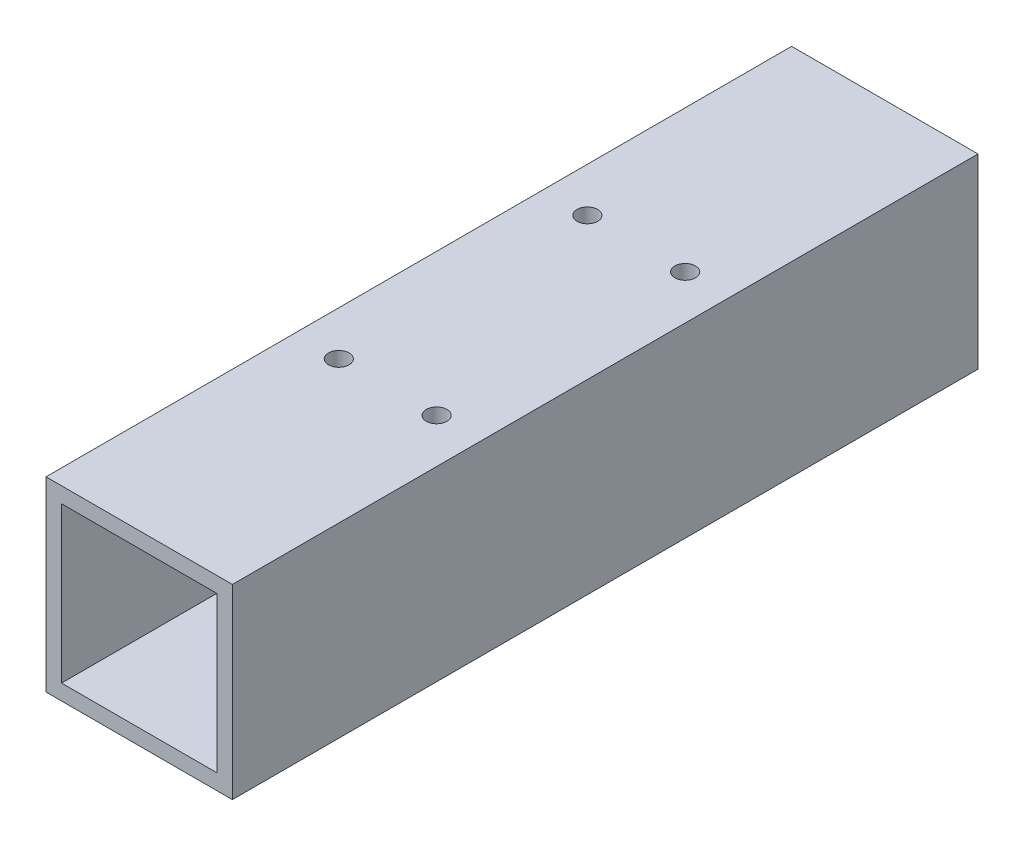
SolidWorks part; units mm, degrees
material "1060 Alloy"
ref_plane "Front Plane" through (0, 0, 0) normal (0, 0, 1) x (1, 0, 0)
ref_plane "Top Plane" through (0, 0, 0) normal (0, 1, 0) x (1, 0, 0)
ref_plane "Right Plane" through (0, 0, 0) normal (1, 0, 0) x (0, 0, -1)
sketch "Sketch1" plane through (0, 0, 0) normal (0, 0, 1) x (1, 0, 0)
  line L0 (-31.75, 31.75) -> (31.75, 31.75)
  line L2 (-38.1, 38.1) -> (38.1, 38.1)
  line L3 (-38.1, 38.1) -> (-38.1, -38.1)
  line L4 (-38.1, -38.1) -> (38.1, -38.1)
  line L5 (38.1, 38.1) -> (38.1, -38.1)
  line L10 (31.75, 31.75) -> (31.75, -31.75)
  line L11 (-31.75, -31.75) -> (31.75, -31.75)
  line L12 (-31.75, 31.75) -> (-31.75, -31.75)
  point P12 (0, 38.1)
  point P14 (38.1, 0)
  dimension "Wall Thickness" = 6.35
  dimension "Outside Width" = 76.2
  dimension "Outside Height" = 76.2
  dimension "Inside Height" = 63.5
  dimension "Inside Width" = 63.5
sketch "Sketch2" plane through (0, 0, 0) normal (1, 0, 0) x (0, 0, -1)
  line L0 (152.4, 0) -> (-152.4, 0)
  point P4 (0, 0)
  point P7 (-152.4, 0)
  point P10 (152.4, 0)
  dimension "Length" = 304.8
sketch "Sketch3" plane through (0, 0, 0) normal (0, 0, 1) x (1, 0, 0)
  line L21 (38.1, 38.1) -> (-38.1, 38.1)
  line L22 (38.1, -38.1) -> (38.1, 38.1)
  line L23 (-38.1, -38.1) -> (38.1, -38.1)
  line L24 (-38.1, 38.1) -> (-38.1, -38.1)
  line L25 (38.1, 38.1) -> (-38.1, 38.1)
  line L26 (38.1, -38.1) -> (38.1, 38.1)
  line L27 (-38.1, -38.1) -> (38.1, -38.1)
  line L28 (-38.1, 38.1) -> (-38.1, -38.1)
  line L29 (31.75, 31.75) -> (-31.75, 31.75)
  line L30 (31.75, -31.75) -> (31.75, 31.75)
  line L31 (-31.75, -31.75) -> (31.75, -31.75)
  line L32 (-31.75, 31.75) -> (-31.75, -31.75)
  line L33 (31.75, 31.75) -> (-31.75, 31.75)
  line L34 (31.75, -31.75) -> (31.75, 31.75)
  line L35 (-31.75, -31.75) -> (31.75, -31.75)
  line L36 (-31.75, 31.75) -> (-31.75, -31.75)
  dimension "D1" = 0
  dimension "D2" = 0
extrude "Boss-Extrude1" add sketch "Sketch3" along normal up to vertex (152.4 mm away) and the other way up to vertex (152.4 mm away) up to point (0, 0, 152.4) other way up to point (0, 0, -152.4)
sketch "Drawing Reference" plane through (0, 0, 0) normal (1, 0, 0) x (0, 0, -1)
  line L0 (-152.4, 0) -> (152.4, 0) construction
  line L1 (0, -38.1) -> (0, 38.1) construction
  line L2 (-152.4, -38.1) -> (152.4, -38.1) construction
  line L5 (-152.4, 38.1) -> (152.4, 38.1) construction
  point P7 (-129.54, 0)
  point P8 (129.54, 0)
  dimension "D1" = 22.86
hole_wizard "5/16 Clearance Hole3" positions "Sketch12" profile "Sketch13" hole size "5/16" standard "ANSI Inch" end condition through all
sketch "Sketch12" plane through (0, -38.1, 0) normal (0, -1, 0) x (-1, 0, 0)
  line L1 (-20, -50.8) -> (20, -50.8)
  line L2 (-20, -50.8) -> (-20, 50.8)
  line L3 (-20, 50.8) -> (20, 50.8)
  line L4 (20, -50.8) -> (20, 50.8)
  line L5 (-20, -50.8) -> (20, 50.8) construction
  line L6 (-20, 50.8) -> (20, -50.8) construction
  point P2 (20, 50.8)
  point P127 (-20, -50.8)
  point P128 (-20, 50.8)
  point P129 (20, -50.8)
  point P143 (0, 0)
  dimension "D1" = 101.6
  dimension "D2" = 40
sketch "Sketch13" plane through (-20, -38.1, -50.8) normal (1, 0, 0) x (0, 0, -1)
  line L0 (0, 0) -> (0, 76.2)
  line L1 (0, 76.2) -> (4.2164, 76.2)
  line L2 (4.2164, 76.2) -> (4.2164, 0)
  line L5 (4.2164, 0) -> (0, 0)
  line L11 (0, -6.35) -> (0, 107.95) construction
  dimension "Thru Hole Dia." = 8.4328
  dimension "Thru Hole Depth" = 76.2
hole_wizard "1/2 Clearance Hole1" positions "Sketch14" profile "Sketch15" hole size "1/2" standard "ANSI Inch"
sketch "Sketch14" plane through (0, -38.1, 0) normal (0, -1, 0) x (-1, 0, 0)
  point P0 (-20, 50.8)
  point P3 (20, 50.8)
  point P6 (-20, -50.8)
  point P9 (20, -50.8)
sketch "Sketch15" plane through (20, -38.1, -50.8) normal (1, 0, 0) x (0, 0, -1)
  line L0 (0, 0) -> (0, 10.4035)
  line L1 (0, 10.4035) -> (6.7462, 6.35)
  line L2 (6.7462, 6.35) -> (6.7462, 0)
  line L5 (6.7462, 0) -> (0, 0)
  line L10 (0, 10.4035) -> (-6.7462, 6.35) construction
  line L11 (0, -6.35) -> (0, 107.95) construction
  dimension "Hole Dia." = 13.4925
  dimension "Hole Depth" = 6.35
  dimension "Drill Angle" = 118
sketch "Sketch16" plane through (0, -38.1, 0) normal (0, -1, 0) x (1, 0, 0)
  line L0 (0, -152.4) -> (0, 152.4) construction
  line L1 (-38.1, -152.4) -> (38.1, -152.4) construction
  line L2 (-38.1, 152.4) -> (38.1, 152.4) construction
  line L4 (38.1, 152.4) -> (38.1, -152.4) construction
  line L5 (38.1, 0) -> (-38.1, 0) construction
  line L6 (-38.1, 152.4) -> (-38.1, -152.4) construction
  point P12 (0, 0)
equation "\"D1@Drawing Reference\"=\"Outside Width@Sketch1\" * .3"
